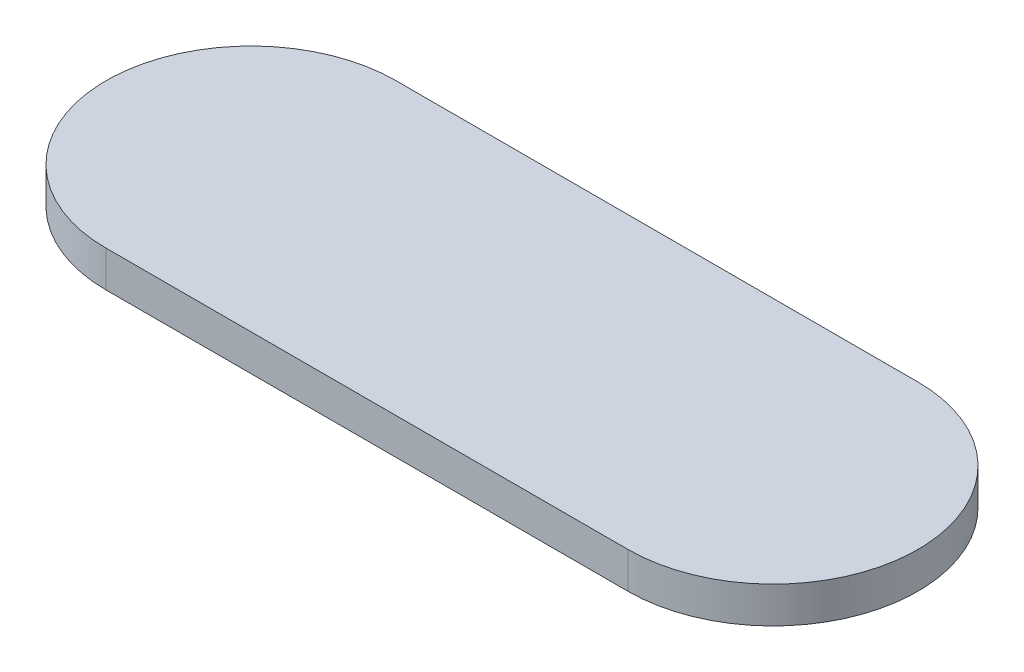
SolidWorks part; units mm, degrees
material "Alloy Steel"
ref_plane "Front Plane" through (0, 0, 0) normal (0, 0, 1) x (1, 0, 0)
ref_plane "Top Plane" through (0, 0, 0) normal (0, 1, 0) x (1, 0, 0)
ref_plane "Right Plane" through (0, 0, 0) normal (1, 0, 0) x (0, 0, -1)
sketch "Sketch1" plane through (0, 0, 0) normal (0, 1, 0) x (1, 0, 0)
  line L0 (-11.43, 0) -> (11.43, 0) construction
  line L1 (-11.43, 6.35) -> (11.43, 6.35)
  line L2 (-11.43, -6.35) -> (11.43, -6.35)
  line L3 (-17.78, 14.4313) -> (-17.78, -15.6858) construction
  line L4 (17.78, 14.4313) -> (17.78, -10.2829) construction
  arc A0 (-11.43, 6.35) -> (-11.43, -6.35) centre (-11.43, 0) ccw
  arc A1 (11.43, -6.35) -> (11.43, 6.35) centre (11.43, 0) ccw
  point P2 (0, 0)
  dimension "D2" = 35.56
  dimension "D1" = 12.7
extrude "Boss-Extrude1" add sketch "Sketch1" along normal blind 1.5875
scale "Scale1" [suppressed]
